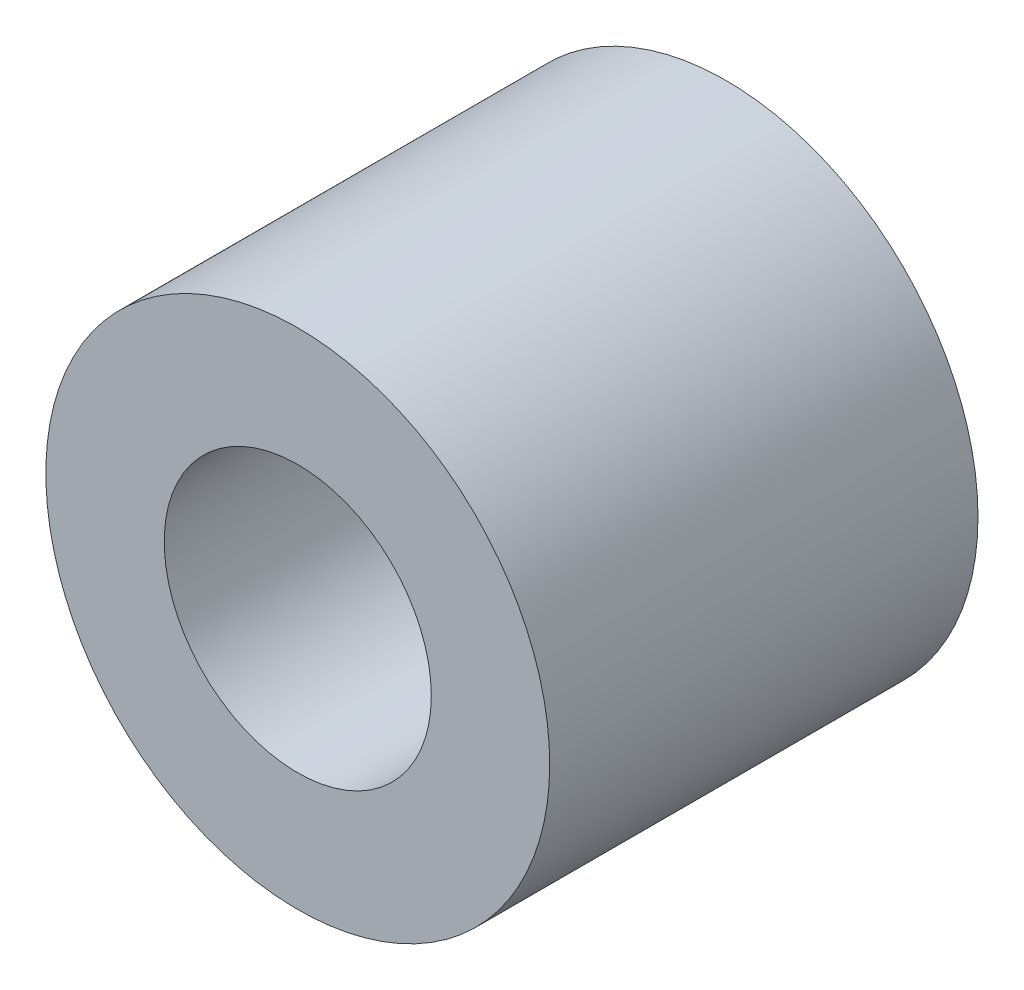
SolidWorks part; units mm, degrees
ref_plane "Alzado" through (0, 0, 0) normal (0, 0, 1) x (1, 0, 0)
ref_plane "Planta" through (0, 0, 0) normal (0, 1, 0) x (1, 0, 0)
ref_plane "Vista lateral" through (0, 0, 0) normal (1, 0, 0) x (0, 0, -1)
sketch "Croquis1" plane through (0, 0, 0) normal (0, 0, 1) x (1, 0, 0)
  circle A0 centre (0, 0) radius 5
  circle A1 centre (0, 0) radius 2.65
  dimension "D1" = 5.3
  dimension "D2" = 10
extrude "Saliente-Extruir1" add sketch "Croquis1" along normal blind 8.5
